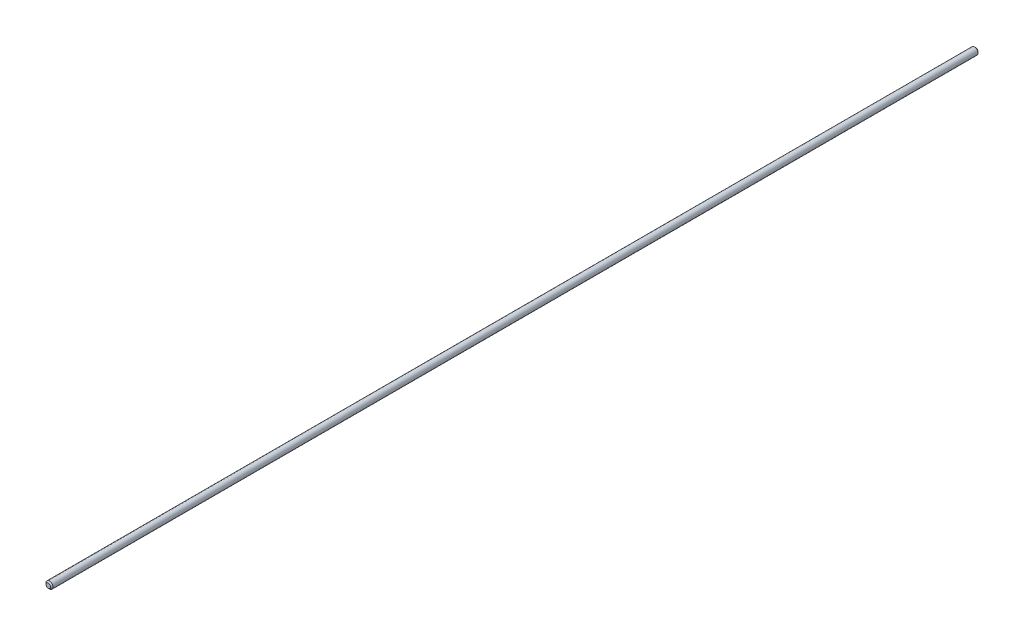
SolidWorks part; units mm, degrees
ref_plane "Ön Düzlem" through (0, 0, 0) normal (0, 0, 1) x (1, 0, 0)
ref_plane "Üst Düzlem" through (0, 0, 0) normal (0, 1, 0) x (1, 0, 0)
ref_plane "Sağ Düzlem" through (0, 0, 0) normal (1, 0, 0) x (0, 0, -1)
sketch "Çizim1" plane through (0, 0, 0) normal (0, 0, 1) x (1, 0, 0)
  circle A0 centre (0, 0) radius 3
  dimension "D1" = 6
extrude "Yükseklik-Ekstrüzyon1" add sketch "Çizim1" along normal blind 800
chamfer "Pah1" distance 1 angle 45 2 edges at (3, 0, 0) (3, 0, 800)
